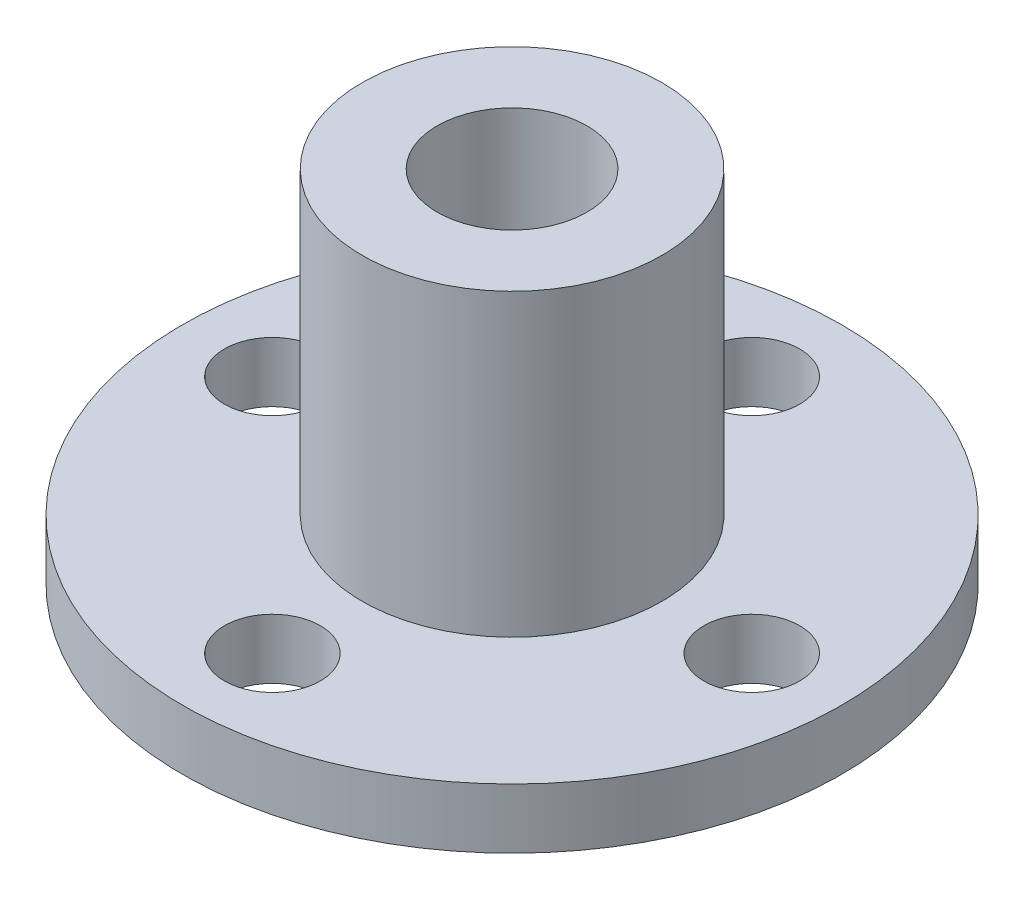
SolidWorks part; units mm, degrees
material "Acciaio inossidabile fuso"
ref_plane "Piano frontale" through (0, 0, 0) normal (0, 0, 1) x (1, 0, 0)
ref_plane "Piano superiore" through (0, 0, 0) normal (0, 1, 0) x (1, 0, 0)
ref_plane "Piano destro" through (0, 0, 0) normal (1, 0, 0) x (0, 0, -1)
sketch "Schizzo2" plane through (0, 0, 0) normal (0, 0, 1) x (1, 0, 0)
  line L0 (-11, 0) -> (-2.5, 0)
  line L1 (-11, 0) -> (-11, 2)
  line L2 (-11, 2) -> (-5, 2)
  line L3 (-5, 2) -> (-5, 12)
  line L4 (-5, 12) -> (-2.5, 12)
  line L5 (-2.5, 12) -> (-2.5, 0)
  line L6 (-2.5, 0) -> (0, 0) construction
  line L7 (0, 0) -> (0, 18.2184) construction
  dimension "D1" = 11
  dimension "D2" = 5
  dimension "D3" = 2.5
  dimension "D4" = 12
  dimension "D5" = 2
revolve "Rivoluzione1" add sketch "Schizzo2" angle 360 about L7
sketch "Schizzo3" plane through (0, 2, 0) normal (0, 1, 0) x (1, 0, 0)
  circle A0 centre (0, 0) radius 8 construction
  circle A3 centre (0, 0) radius 5 construction
  circle A4 centre (-8, 0) radius 1.6
  circle A5 centre (0, 8) radius 1.6
  circle A6 centre (8, 0) radius 1.6
  circle A7 centre (0, -8) radius 1.6
  dimension "D1" = 3
  dimension "D2" = 3.2
extrude "Taglio-Estrusione1" cut sketch "Schizzo3" against normal blind 10
